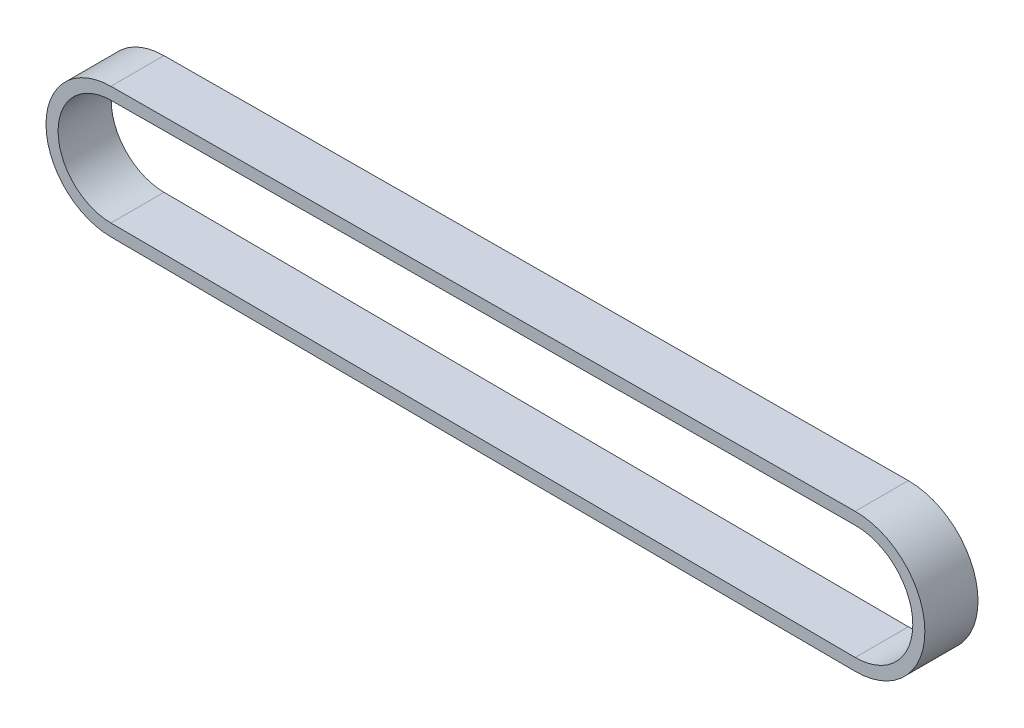
SolidWorks part; units mm, degrees
material "Natural Rubber"
ref_plane "Front" through (0, 0, 0) normal (0, 0, 1) x (1, 0, 0)
ref_plane "Top" through (0, 0, 0) normal (0, 1, 0) x (1, 0, 0)
ref_plane "Right" through (0, 0, 0) normal (1, 0, 0) x (0, 0, -1)
sketch "Sketch2" plane through (0, 0, 0) normal (0, 0, 1) x (1, 0, 0)
  line L0 (-77.1107, 10.9998) -> (76.9846, 11.8498)
  line L1 (-77.1107, -10.9998) -> (76.9846, -11.8498)
  line L2 (-77.1245, 13.4998) -> (76.9708, 14.3498)
  line L3 (-77.1245, -13.4998) -> (76.9708, -14.3498)
  line L4 (-77.05, 0) -> (77.05, 0) construction
  arc A0 (76.9846, -11.8498) -> (76.9846, 11.8498) centre (77.05, 0) ccw
  arc A1 (-77.1107, 10.9998) -> (-77.1107, -10.9998) centre (-77.05, 0) ccw
  arc A2 (76.9708, -14.3498) -> (76.9708, 14.3498) centre (77.05, 0) ccw
  arc A3 (-77.1245, 13.4998) -> (-77.1245, -13.4998) centre (-77.05, 0) ccw
  point P12 (0, 0)
  dimension "D1" = 154.1
  dimension "D2" = 154.1
  dimension "D5" = 14.35
  dimension "D6" = 11.85
  dimension "D7" = 13.5
  dimension "D8" = 11
  dimension "D3" = 2.5
  dimension "D4" = 2.5
extrude "Boss-Extrude1" add sketch "Sketch2" along normal blind 11
